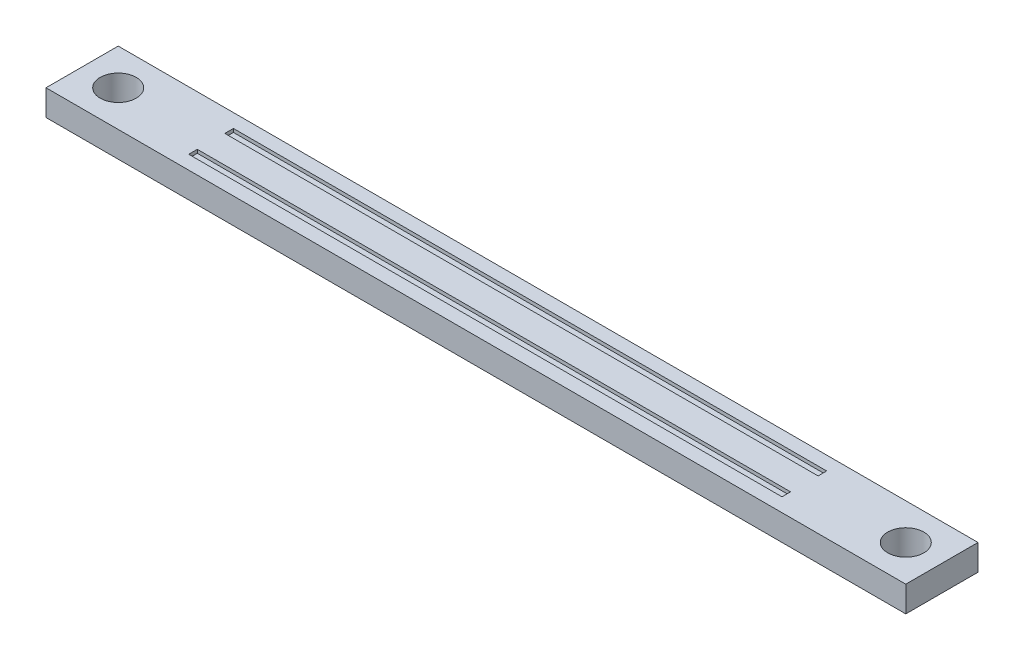
SolidWorks part; units mm, degrees
ref_plane "Plan de face" through (0, 0, 0) normal (0, 0, 1) x (1, 0, 0)
ref_plane "Plan de dessus" through (0, 0, 0) normal (0, 1, 0) x (1, 0, 0)
ref_plane "Plan de droite" through (0, 0, 0) normal (1, 0, 0) x (0, 0, -1)
sketch "Esquisse1" plane through (0, 0, 0) normal (0, 1, 0) x (1, 0, 0)
  line L1 (-260, -21) -> (260, -21)
  line L2 (-260, -21) -> (-260, 21)
  line L3 (-260, 21) -> (260, 21)
  line L4 (260, -21) -> (260, 21)
  line L5 (-260, -21) -> (260, 21) construction
  line L6 (-260, 21) -> (260, -21) construction
  point P0 (0, 0)
  dimension "D1" = 520
  dimension "D2" = 42
extrude "Boss.-Extru.1" add sketch "Esquisse1" along normal blind 15
sketch "Esquisse2" plane through (0, 15, 0) normal (0, 1, 0) x (1, 0, 0)
  line L0 (-260, 21) -> (-198, -21) construction
  line L1 (-260, -21) -> (260, -21) construction
  line L2 (-198, -21) -> (-198, 21) construction
  line L3 (260, 21) -> (-260, 21) construction
  line L4 (-198, 21) -> (-260, 21) construction
  line L5 (260, 21) -> (198, -21) construction
  line L6 (198, -21) -> (260, -21) construction
  line L7 (260, -21) -> (260, 21) construction
  circle A0 centre (-229, 0) radius 10.5
  circle A1 centre (229, 0) radius 10.5
  dimension "D1" = 21
  dimension "D2" = 21
extrude "Enlèv. mat.-Extru.1" cut sketch "Esquisse2" against normal blind 15
sketch "Esquisse3" plane through (0, 15, 0) normal (0, 1, 0) x (1, 0, 0)
  line L0 (260, 21) -> (-260, 21) construction
  line L1 (-260, -21) -> (-250, -21)
  line L2 (-260, -21) -> (-260, 21)
  line L3 (-260, 21) -> (-250, 21)
  line L4 (-250, -21) -> (-250, 21)
  line L6 (260, -21) -> (250, -21)
  line L7 (260, -21) -> (260, 21)
  line L8 (260, 21) -> (250, 21)
  line L9 (250, -21) -> (250, 21)
  dimension "D1" = 10
  dimension "D2" = 10
extrude "Enlèv. mat.-Extru.2" cut sketch "Esquisse3" against normal through all
sketch "Esquisse4" plane through (0, 15, 0) normal (0, 1, 0) x (1, 0, 0)
  line L0 (-250, -21) -> (250, -21) construction
  line L1 (-175, -21) -> (170, -21)
  line L2 (-175, -21) -> (-175, -13)
  line L3 (-175, -13) -> (170, -13)
  line L4 (170, -21) -> (170, -13)
  line L5 (250, 21) -> (-250, 21) construction
  line L6 (170, 21) -> (-175, 21)
  line L7 (170, 21) -> (170, 13)
  line L8 (170, 13) -> (-175, 13)
  line L9 (-175, 21) -> (-175, 13)
  line L10 (-250, -21) -> (-250, 21) construction
  line L11 (-175, -8) -> (170, -8)
  line L12 (-175, -8) -> (-175, 8)
  line L13 (-175, 8) -> (170, 8)
  line L14 (170, -8) -> (170, 8)
  line L15 (250, 21) -> (250, -21) construction
  line L16 (-175, 13) -> (-175, 8)
  line L17 (-175, -8) -> (-175, -13)
  line L18 (170, -13) -> (170, -8)
  line L19 (170, 8) -> (170, 13)
  dimension "D1" = 8
  dimension "D2" = 8
  dimension "D3" = 5
  dimension "D4" = 5
  dimension "D5" = 16
  dimension "D6" = 75
  dimension "D7" = 75
  dimension "D8" = 80
  dimension "D9" = 80
  dimension "D10" = 80
extrude "Enlèv. mat.-Extru.3" cut sketch "Esquisse4" against normal blind 2 contours L3 L18 L11 L17 | L13 L19 L8 L16
